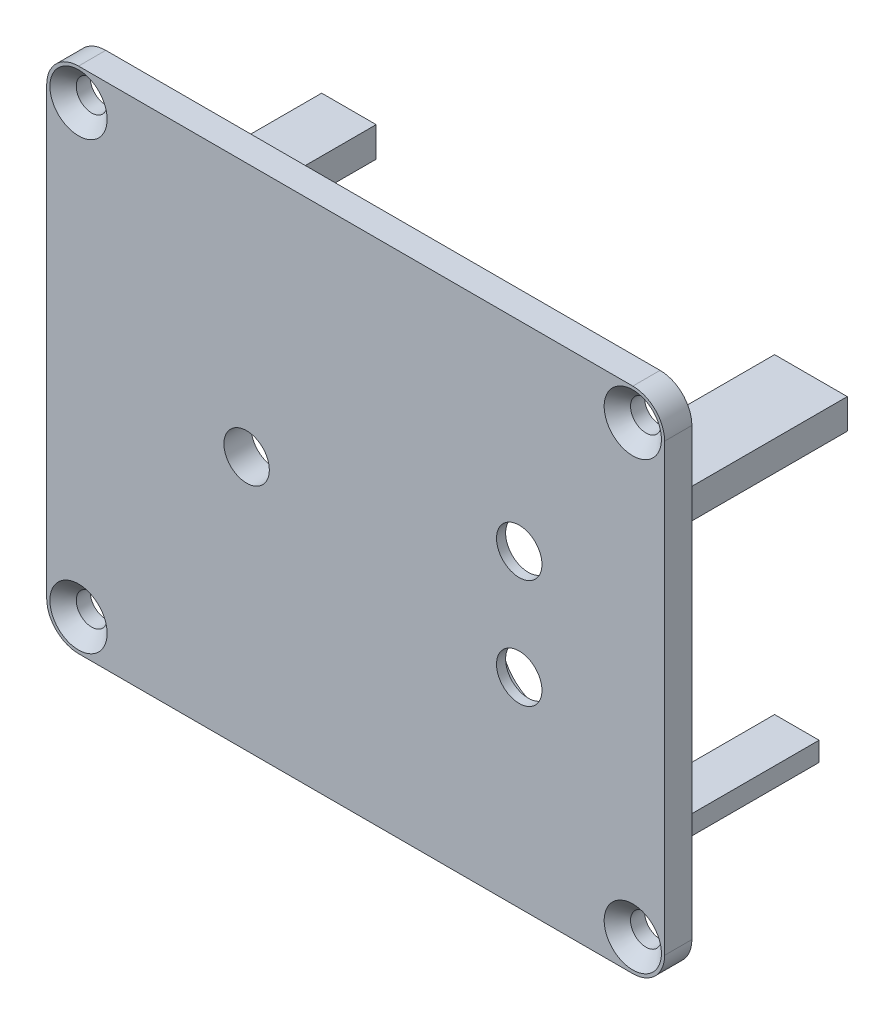
SolidWorks part; units mm, degrees
ref_plane "Plan de face" through (0, 0, 0) normal (0, 0, 1) x (1, 0, 0)
ref_plane "Plan de dessus" through (0, 0, 0) normal (0, 1, 0) x (1, 0, 0)
ref_plane "Plan de droite" through (0, 0, 0) normal (1, 0, 0) x (0, 0, -1)
sketch "Esquisse1" plane through (0, 0, 0) normal (0, 0, 1) x (1, 0, 0)
  line L1 (-34, 28) -> (34, 28)
  line L2 (-34, 28) -> (-34, -28)
  line L3 (-34, -28) -> (34, -28)
  line L4 (34, 28) -> (34, -28)
  line L5 (-34, 28) -> (34, -28) construction
  line L6 (-34, -28) -> (34, 28) construction
  point P0 (0, 0)
  dimension "D1" = 68
  dimension "D2" = 56
extrude "Boss.-Extru.1" add sketch "Esquisse1" along normal mid plane 3
sketch "Esquisse2" plane through (-25.817, 0, 1.5) normal (0, 0, 1) x (1, 0, 0)
  line L0 (25.817, 0) -> (32.5807, 0) construction
  circle A0 centre (13.817, 0) radius 2.5
  circle A1 centre (43.817, 6) radius 2.5
  circle A2 centre (43.817, -6) radius 2.5
  point P10 (0, 0)
  point P11 (0, 0)
  point P12 (32.3423, -1.7801)
  point P13 (0, 0)
  point P14 (43.817, 6.0816)
  dimension "D1" = 5
  dimension "D2" = 5
  dimension "D3" = 12
  dimension "D4" = 18
  dimension "D5" = 12
extrude "Enlèv. mat.-Extru.1" cut sketch "Esquisse2" against normal up to next
fillet "Congé1" radius 3.5 4 edges at (34, -28, 0) (-34, -28, 0) (-34, 28, 0) (34, 28, 0)
hole_wizard "Fraisage pour vis à tête fraisée M31" positions "Esquisse3" profile "Esquisse4" countersink size "M3" standard "Ansi Metric"
sketch "Esquisse3" plane through (0, 0, 1.5) normal (0, 0, 1) x (1, 0, 0)
  point P0 (-30.5, -24.5)
  point P4 (-30.5, 24.5)
  point P7 (30.5, 24.5)
  point P10 (30.5, -24.5)
sketch "Esquisse4" plane through (-30.5, -24.5, 1.5) normal (1, 0, 0) x (0, -1, 0)
  line L0 (0, 0) -> (0, 22.6915)
  line L1 (0, 22.6915) -> (1.7, 21.67)
  line L2 (1.7, 21.67) -> (1.7, 1.45)
  line L3 (1.7, 1.45) -> (3.15, 0)
  line L5 (3.15, 0) -> (0, 0)
  line L6 (-1.7, 1.45) -> (-3.15, 0) construction
  line L10 (0, 22.6915) -> (-1.7, 21.67) construction
  line L11 (0, -6.35) -> (0, 107.95) construction
  dimension "Diamètre du perçage" = 3.4
  dimension "Profondeur du perçage" = 21.67
  dimension "Diamètre du fraisage entrant" = 6.3
  dimension "Angle du fraisage entrant" = 90
  dimension "Angle de pointe" = 118
sketch "Esquisse5" plane through (0, 0, -1.5) normal (0, 0, -1) x (-1, 0, 0)
  line L0 (0, 0) -> (-5.6997, 0) construction
  line L1 (0, 0) -> (0, -3.3751) construction
  line L2 (20.7418, -25) -> (20.7418, -20.5) construction
  line L3 (31, -15) -> (27.5, -15) construction
  line L4 (27.5, -15) -> (27.5, -20.5) construction
  line L5 (20.7418, -20.5) -> (27.5, -20.5) construction
  line L6 (20.7418, -22.7392) -> (25.2608, -22.7392) construction
  line L7 (25.2608, -22.7392) -> (27.5, -20.5) construction
  line L8 (20.7418, 10.5) -> (27.5, 10.5) construction
  line L9 (-31, 14) -> (31, 14) construction
  line L10 (27.5, 5) -> (31, 5) construction
  line L11 (27.5, 5) -> (27.5, 10.5) construction
  line L12 (27.5, 10.5) -> (25.2608, 12.7392) construction
  line L13 (25.2608, 12.7392) -> (20.7418, 12.7392) construction
  line L14 (-21.1035, -22.7392) -> (-23.7608, -22.7392) construction
  line L15 (-23.7608, -22.7392) -> (-26, -20.5) construction
  line L16 (-26, -20.5) -> (-26, -15) construction
  line L17 (-26, -15) -> (-31, -15) construction
  line L18 (-21.1035, -25) -> (-21.1035, -20.5) construction
  line L19 (-21.1035, -20.5) -> (-26, -20.5) construction
  line L20 (-21.1035, 10.5) -> (-26, 10.5) construction
  line L21 (-26, 10.5) -> (-26, 5) construction
  line L22 (-26, 5) -> (-31, 5) construction
  line L23 (-21.1035, 10.5) -> (-21.1035, 25) construction
  line L24 (-26, 10.5) -> (-23.7608, 12.7392) construction
  line L25 (-21.1035, 12.7392) -> (-23.7608, 12.7392) construction
  line L26 (20.7418, 10.5) -> (20.7418, 25) construction
  line L27 (-31, 16) -> (31, 16) construction
  point P25 (-26, -17.75)
  point P34 (27.5, -17.75)
  point P37 (0, 0)
  point P39 (0, 0)
  point P40 (0, 0)
  dimension "D1" = 135
  dimension "D2" = 27.5
  dimension "D3" = 20.7418
  dimension "D4" = 20.5
  dimension "D5" = 21.1035
  dimension "D6" = 135
  dimension "D7" = 26
  dimension "D8" = 15
  dimension "D9" = 5
  dimension "D10" = 10.5
  dimension "D11" = 135
  dimension "D12" = 135
  dimension "D13" = 31
  dimension "D14" = 53.5
  dimension "D15" = 2.2392
  dimension "D16" = 2.2392
  dimension "D17" = 2
sketch "Esquisse6" plane through (0, 0, -1.5) normal (0, 0, -1) x (-1, 0, 0)
  line L0 (-21.1035, -20.5) -> (-26, -20.5) construction
  line L1 (-21.1035, -25) -> (-21.1035, -20.5) construction
  line L4 (20.7418, 10.5) -> (27.5, 10.5) construction
  line L6 (-21.1035, 10.5) -> (-26, 10.5) construction
  line L7 (-21.1035, 10.5) -> (-21.1035, 25) construction
  line L8 (-21.1035, -20.5) -> (-26, -20.5)
  line L9 (-21.1035, -24.5392) -> (-21.1035, -20.5)
  line L12 (22.7418, 10.5) -> (27.5, 10.5)
  line L14 (-21.1035, 10.5) -> (-26, 10.5)
  line L15 (-21.1035, 10.5) -> (-21.1035, 13.8)
  line L16 (-26, 10.5) -> (-29.1035, 10.5)
  line L17 (-29.1035, 10.5) -> (-29.1035, 13.8)
  line L18 (-29.1035, 13.8) -> (-21.1035, 13.8)
  line L19 (27.5, 10.5) -> (28.7418, 10.5)
  line L20 (28.7418, 10.5) -> (28.7418, 13.8)
  line L21 (28.7418, 13.8) -> (22.7418, 13.8)
  line L22 (-26, -20.5) -> (-26, -22.6213)
  line L27 (22.7418, 13.8) -> (22.7418, 10.5)
  line L28 (-26, -22.6213) -> (-24.0821, -24.5392)
  line L29 (-23.7608, -22.7392) -> (-26, -20.5) construction
  line L30 (-24.0821, -24.5392) -> (-21.1035, -24.5392)
  line L31 (-21.1035, -22.7392) -> (-23.7608, -22.7392) construction
  dimension "D1" = 0.2
  dimension "D2" = 2
  dimension "D3" = 6
  dimension "D4" = 8
  dimension "D5" = 1.5
  dimension "D6" = 1.8
extrude "Boss.-Extru.2" add sketch "Esquisse6" along normal blind 22
sketch "Esquisse7" plane through (0, 0, -1.5) normal (0, 0, -1) x (-1, 0, 0)
  line L0 (-18, -6) -> (-18, 6) construction
  line L1 (-23, -6) -> (-23, 6)
  line L2 (-13, -6) -> (-13, 6)
  arc A0 (-23, -6) -> (-13, -6) centre (-18, -6) ccw
  arc A1 (-13, 6) -> (-23, 6) centre (-18, 6) ccw
  circle A2 centre (-18, 6) radius 2.5 construction
  circle A3 centre (-18, -6) radius 2.5 construction
  point P2 (-18, 0)
  point P7 (0, 0)
  point P8 (0, 0)
  point P12 (0, 0)
  dimension "D1" = 10
extrude "Enlèv. mat.-Extru.2" cut sketch "Esquisse7" against normal blind 2
